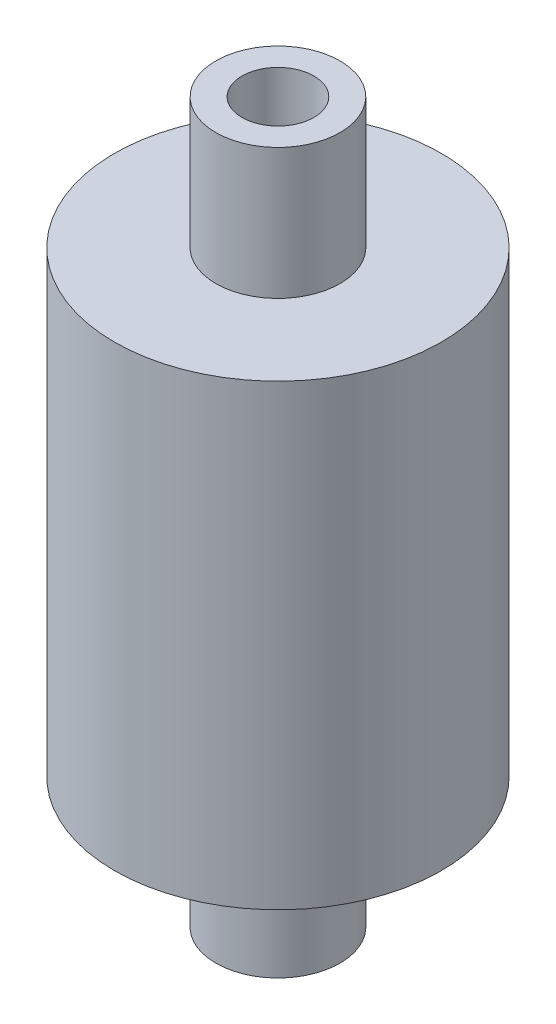
SolidWorks part; units mm, degrees
ref_plane "Front Plane" through (0, 0, 0) normal (0, 0, 1) x (1, 0, 0)
ref_plane "Top Plane" through (0, 0, 0) normal (0, 1, 0) x (1, 0, 0)
ref_plane "Right Plane" through (0, 0, 0) normal (1, 0, 0) x (0, 0, -1)
sketch "Sketch1" plane through (0, 0, 0) normal (1, 0, 0) x (0, 0, -1)
  line L0 (0, 59.0476) -> (0, -57.381) construction
  line L1 (-4.75, 27.5) -> (-4.75, 17.5)
  line L2 (-4.75, 17.5) -> (-12.5, 17.5)
  line L3 (-12.5, 17.5) -> (-12.5, -17.5)
  line L4 (-12.5, -17.5) -> (-4.75, -17.5)
  line L5 (-4.75, -17.5) -> (-4.75, -27.5)
  line L6 (-4.75, 27.5) -> (-2.75, 27.5)
  line L7 (-2.75, 27.5) -> (-2.75, -27.5)
  line L8 (-2.75, -27.5) -> (-4.75, -27.5)
  point P5 (-12.5, 0)
  dimension "D1" = 10
  dimension "D2" = 9.5
  dimension "D3" = 25
  dimension "D4" = 2
  dimension "D5" = 2
  dimension "D6" = 55
revolve "Revolve1" add sketch "Sketch1" angle 360 about L0
